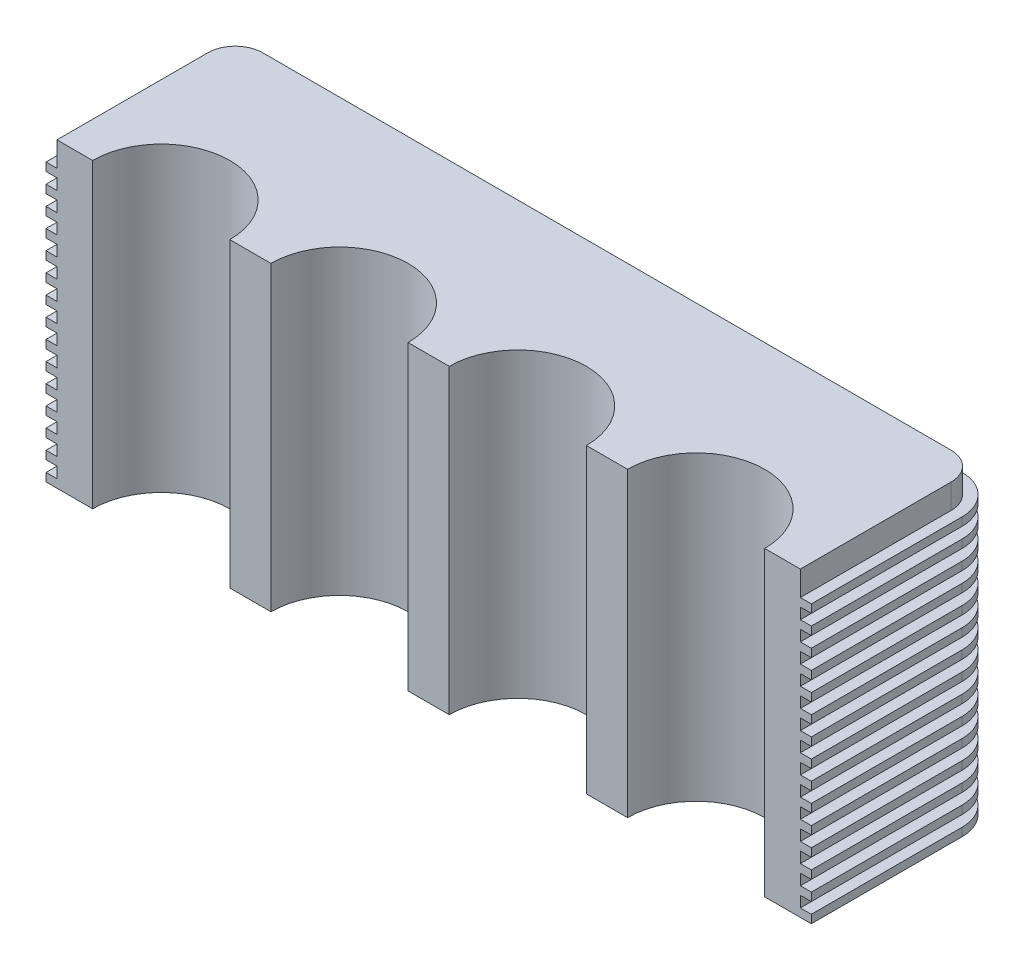
SolidWorks part; units mm, degrees
ref_plane "Front Plane" through (0, 0, 0) normal (0, 0, 1) x (1, 0, 0)
ref_plane "Top Plane" through (0, 0, 0) normal (0, 1, 0) x (1, 0, 0)
ref_plane "Right Plane" through (0, 0, 0) normal (1, 0, 0) x (0, 0, -1)
sketch "Sketch4" plane through (0, 0, 0) normal (0, 1, 0) x (1, 0, 0)
  line L0 (258, 0) -> (271, 0)
  line L1 (0, 0) -> (13, 0)
  line L2 (0, 0) -> (0, 55)
  line L3 (10, 65) -> (261, 65)
  line L4 (271, 0) -> (271, 55)
  line L5 (135.5, 65) -> (135.5, 0) construction
  line L6 (193, 0) -> (208, 0)
  line L7 (63, 0) -> (78, 0)
  line L8 (128, 0) -> (143, 0)
  arc A0 (261, 65) -> (271, 55) centre (261, 55) cw
  arc A1 (10, 65) -> (0, 55) centre (10, 55) ccw
  arc A2 (258, 0) -> (208, 0) centre (233, 0) ccw
  arc A3 (193, 0) -> (143, 0) centre (168, 0) ccw
  arc A4 (13, 0) -> (63, 0) centre (38, 0) cw
  arc A5 (78, 0) -> (128, 0) centre (103, 0) cw
  point P9 (0, 65)
  dimension "D3" = 10
  dimension "D4" = 50
  dimension "D6" = 50
  dimension "D1" = 271
  dimension "D2" = 65
  dimension "D5" = 13
  dimension "D7" = 15
extrude "Boss-Extrude1" add sketch "Sketch4" along normal blind 110
sketch "Sketch5" plane through (0, 0, 0) normal (0, 1, 0) x (1, 0, 0)
  line L1 (275, 0) -> (275, 55)
  line L2 (261, 69) -> (10, 69)
  line L3 (-4, 55) -> (-4, 0)
  line L4 (271, 0) -> (275, 0)
  line L5 (0, 0) -> (-4, 0)
  line L9 (0, 55) -> (0, 0)
  line L10 (0, 0) -> (13, 0)
  line L11 (63, 0) -> (78, 0)
  line L12 (128, 0) -> (143, 0)
  line L13 (193, 0) -> (208, 0)
  line L14 (258, 0) -> (271, 0)
  line L15 (271, 0) -> (271, 55)
  line L16 (261, 65) -> (10, 65)
  line L17 (0, 55) -> (0, 0)
  line L23 (271, 0) -> (271, 55)
  line L24 (261, 65) -> (10, 65)
  arc A0 (275, 55) -> (261, 69) centre (261, 55) ccw
  arc A1 (10, 69) -> (-4, 55) centre (10, 55) ccw
  arc A6 (63, 0) -> (13, 0) centre (38, 0) ccw
  arc A7 (128, 0) -> (78, 0) centre (103, 0) ccw
  arc A8 (193, 0) -> (143, 0) centre (168, 0) ccw
  arc A9 (258, 0) -> (208, 0) centre (233, 0) ccw
  arc A10 (271, 55) -> (261, 65) centre (261, 55) ccw
  arc A11 (10, 65) -> (0, 55) centre (10, 55) ccw
  arc A16 (271, 55) -> (261, 65) centre (261, 55) ccw
  arc A17 (10, 65) -> (0, 55) centre (10, 55) ccw
  dimension "D1" = 0
  dimension "D2" = 4
extrude "Boss-Extrude2" add sketch "Sketch5" along normal blind 3
pattern_linear "LPattern1" count 15 spacing 7 along (0, 1, 0) of "Boss-Extrude2"
